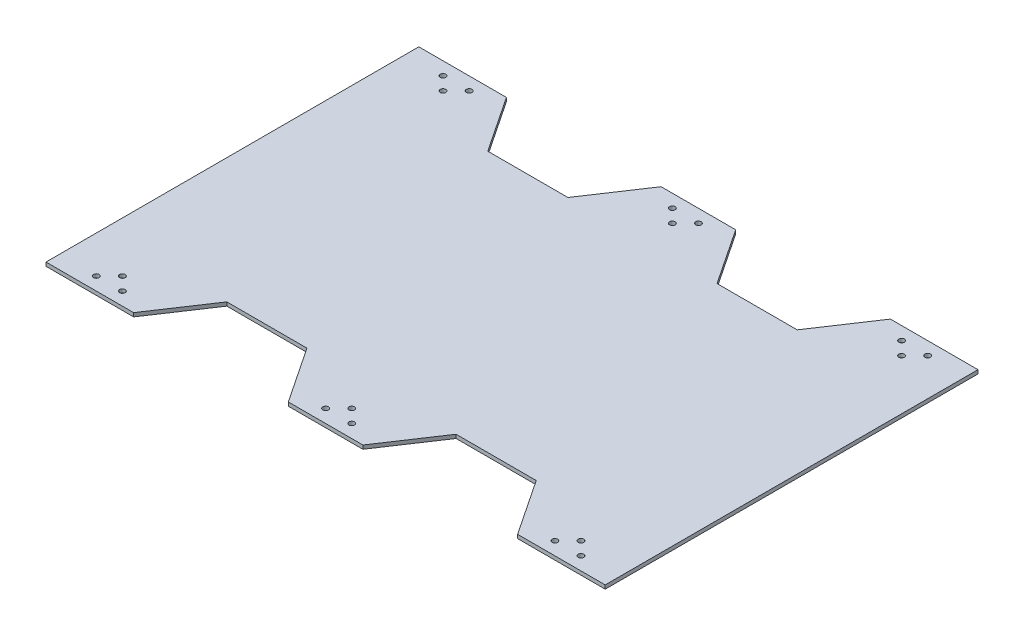
SolidWorks part; units mm, degrees
material "AISI 316 Arkusz stali nierdzewnej (SS)"
ref_plane "Płaszczyzna przednia" through (0, 0, 0) normal (0, 0, 1) x (1, 0, 0)
ref_plane "Płaszczyzna górna" through (0, 0, 0) normal (0, 1, 0) x (1, 0, 0)
ref_plane "Płaszczyzna prawa" through (0, 0, 0) normal (1, 0, 0) x (0, 0, -1)
sketch "Szkic1" plane through (0, 0, 0) normal (0, 1, 0) x (1, 0, 0)
  line L1 (-150, 100) -> (150, 100)
  line L2 (-150, 100) -> (-150, -100)
  line L3 (-150, -100) -> (150, -100)
  line L4 (150, 100) -> (150, -100)
  line L5 (-150, 100) -> (150, -100) construction
  line L6 (-150, -100) -> (150, 100) construction
  point P0 (0, 0)
  dimension "D1" = 200
  dimension "D2" = 300
extrude "Dodanie-wyciągnięcie1" add sketch "Szkic1" against normal blind 2
sketch "Szkic2" plane through (0, 0, 0) normal (0, 1, 0) x (1, 0, 0)
  line L0 (0, 100) -> (0, -100) construction
  line L1 (150, 100) -> (-150, 100) construction
  line L2 (-150, -100) -> (150, -100) construction
  line L3 (-150, 0) -> (150, 0) construction
  line L4 (-150, 100) -> (-150, -100) construction
  line L5 (150, -100) -> (150, 100) construction
  line L6 (0, -86) -> (-7, -86) construction
  line L7 (-7, -86) -> (-7, -93) construction
  line L8 (-7, -93) -> (-7, -100) construction
  line L11 (-130, -93) -> (-130, -100) construction
  line L12 (-123, -86) -> (-123, -93) construction
  line L13 (-123, -93) -> (-130, -93) construction
  circle A0 centre (0, -86) radius 1.5
  circle A1 centre (-7, -93) radius 1.5
  circle A6 centre (7, -93) radius 1.5
  circle A7 centre (-123, -86) radius 1.5
  circle A8 centre (-130, -93) radius 1.5
  circle A10 centre (-116, -93) radius 1.5
  circle A11 centre (130, -93) radius 1.5
  circle A12 centre (123, -86) radius 1.5
  circle A13 centre (116, -93) radius 1.5
  circle A14 centre (0, 86) radius 1.5
  circle A15 centre (7, 93) radius 1.5
  circle A16 centre (-7, 93) radius 1.5
  circle A17 centre (130, 93) radius 1.5
  circle A18 centre (123, 86) radius 1.5
  circle A19 centre (116, 93) radius 1.5
  circle A20 centre (-116, 93) radius 1.5
  circle A21 centre (-123, 86) radius 1.5
  circle A22 centre (-130, 93) radius 1.5
  dimension "D1" = 3
  dimension "D2" = 7
  dimension "D3" = 7
  dimension "D4" = 7
  dimension "D5" = 20
extrude "Wytnij-wyciągnięcie1" cut sketch "Szkic2" against normal up to next
sketch "Szkic3" plane through (0, -2, 0) normal (0, -1, 0) x (1, 0, 0)
  line L0 (0, 100) -> (0, -100) construction
  line L1 (-150, 100) -> (150, 100) construction
  line L2 (150, -100) -> (-150, -100) construction
  line L3 (-123, -86) -> (-123, -100) construction
  line L4 (-61.5, -100) -> (-61.5, 100) construction
  line L5 (-123, -100) -> (-61.5, -100) construction
  line L6 (-61.5, -100) -> (0, -100) construction
  line L7 (-103, -100) -> (-83, -70)
  line L8 (-83, -70) -> (-40, -70)
  line L9 (-20, -100) -> (-40, -70)
  line L10 (-103, -100) -> (-20, -100)
  line L11 (103, -100) -> (83, -70)
  line L12 (83, -70) -> (40, -70)
  line L13 (20, -100) -> (40, -70)
  line L14 (103, -100) -> (20, -100)
  line L15 (-150, 0) -> (150, 0) construction
  line L16 (-150, -100) -> (-150, 100) construction
  line L17 (150, 100) -> (150, -100) construction
  line L18 (103, 100) -> (20, 100)
  line L19 (20, 100) -> (40, 70)
  line L20 (83, 70) -> (40, 70)
  line L21 (103, 100) -> (83, 70)
  line L22 (-103, 100) -> (-83, 70)
  line L23 (-83, 70) -> (-40, 70)
  line L24 (-20, 100) -> (-40, 70)
  line L25 (-103, 100) -> (-20, 100)
  point P16 (-61.5, -70)
  dimension "D1" = 20
  dimension "D2" = 30
  dimension "D3" = 20
extrude "Wytnij-wyciągnięcie2" cut sketch "Szkic3" along direction (0, 1, 0) on the side against the normal up to next (2 mm away)
